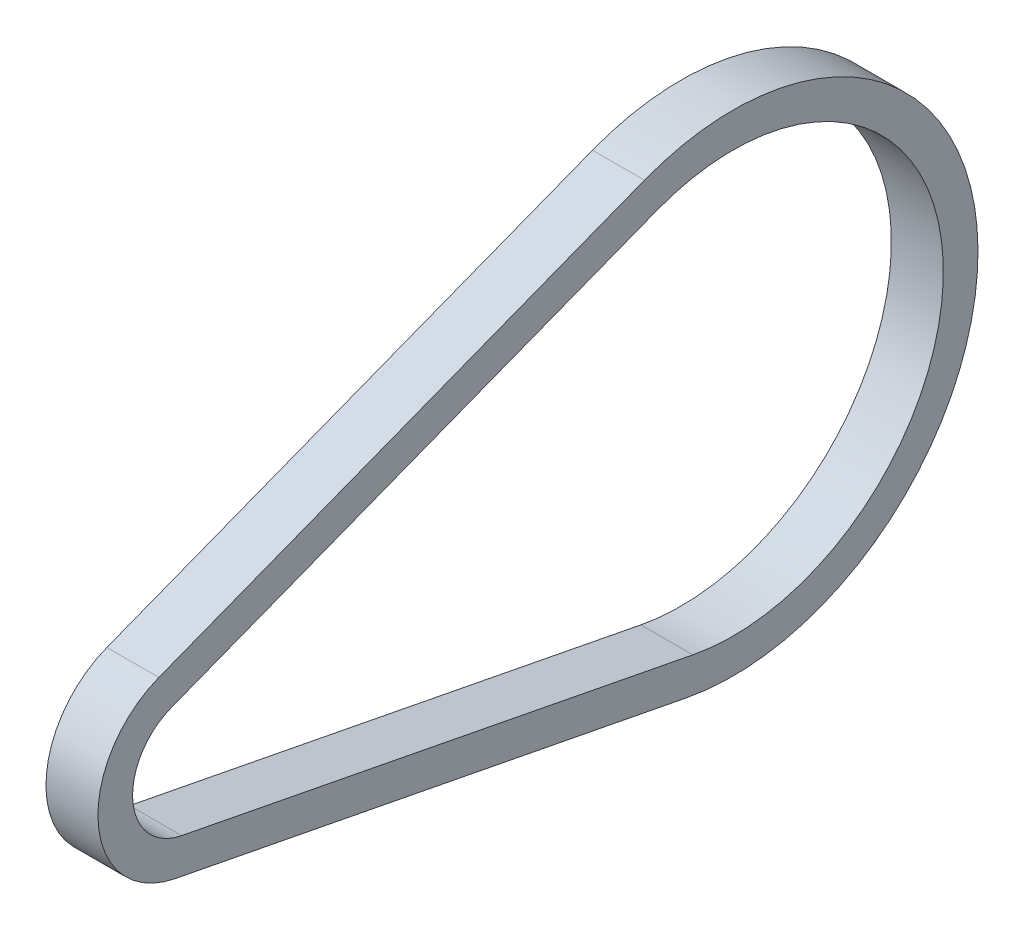
SolidWorks part; units mm, degrees
ref_plane "Front Plane" through (0, 0, 0) normal (0, 0, 1) x (1, 0, 0)
ref_plane "Top Plane" through (0, 0, 0) normal (0, 1, 0) x (1, 0, 0)
ref_plane "Right Plane" through (0, 0, 0) normal (1, 0, 0) x (0, 0, -1)
ref_plane "Plane1" through (110.25, 0, 0) normal (1, 0, 0) x (0, 0, -1)
sketch "Sketch1" plane through (110.25, 0, 0) normal (1, 0, 0) x (0, 0, -1)
  line L0 (789.6978, 298.6978) -> (611.6922, 229.8511)
  line L1 (616.5638, 175.1469) -> (803.9339, 138.8382)
  circle A0 centre (819.8197, 220.8166) radius 83.5034 construction
  arc A1 (611.6922, 229.8511) -> (616.5638, 175.1469) centre (622, 203.2) ccw
  arc A2 (803.9339, 138.8382) -> (789.6978, 298.6978) centre (819.8197, 220.8166) ccw
  circle A3 centre (622, 203.2) radius 108.3 construction
  point P8 (664.0095, 316.1265)
  point P11 (609.226, 251.659)
  point P12 (611.6573, 230.2634)
  dimension "D1" = 28.575
extrude "Extrude-Thin1" add sketch "Sketch1" along normal mid plane 19.05 thin thin type mid plane wall 12.7
